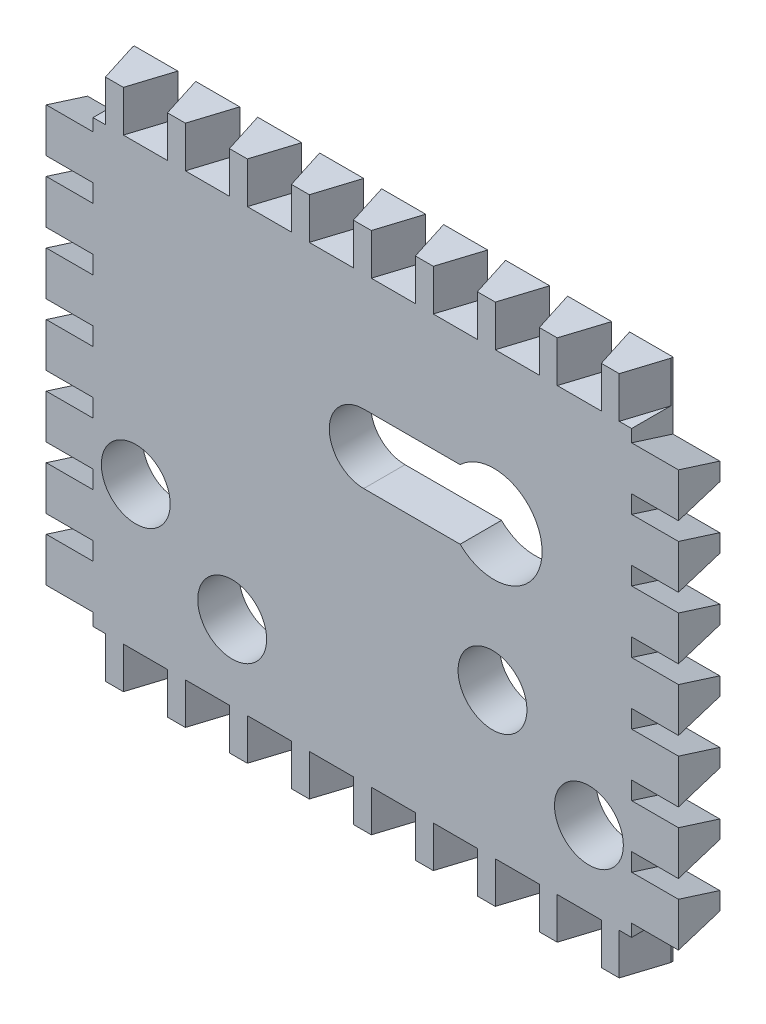
SolidWorks part; units mm, degrees
ref_plane "前视基准面" through (0, 0, 0) normal (0, 0, 1) x (1, 0, 0)
ref_plane "上视基准面" through (0, 0, 0) normal (0, 1, 0) x (1, 0, 0)
ref_plane "右视基准面" through (0, 0, 0) normal (1, 0, 0) x (0, 0, -1)
sketch "草图1" plane through (0, 0, 0) normal (0, 0, 1) x (1, 0, 0)
  line L1 (0, 0) -> (45.9, 0)
  line L2 (0, 0) -> (0, -38)
  line L3 (0, -38) -> (45.9, -38)
  line L4 (45.9, 0) -> (45.9, -38)
  dimension "D1" = 38
  dimension "D2" = 45.9
extrude "凸台-拉伸1" add sketch "草图1" along normal blind 3
sketch "草图2" plane through (0, 0, 3) normal (0, 0, 1) x (1, 0, 0)
  line L0 (22.95, 0) -> (22.95, -39.2263) construction
  line L1 (45.9, 0) -> (0, 0) construction
  line L2 (0, -19) -> (59.2839, -19) construction
  line L3 (0, 0) -> (0, -38) construction
sketch "草图3" plane through (0, 0, 0) normal (-1, 0, 0) x (0, 0, 1)
  line L2 (3, -7.1) -> (0, -6.15)
  line L7 (0, 0) -> (0, -38) construction
  line L8 (0, -4.85) -> (3, -3.9)
  line L9 (3, 0) -> (3, -39.2263) construction
  line L12 (0, -9.35) -> (3, -8.4)
  line L13 (0, -3.25) -> (4.2725, -3.25) construction
  line L15 (3, -11.6) -> (0, -10.65)
  line L16 (0, -10.65) -> (0, -13.85)
  line L17 (3, 0) -> (0, 0) construction
  line L18 (0, -13.85) -> (3, -12.9)
  line L19 (3, -12.9) -> (3, -11.6)
  line L20 (3, -16.1) -> (0, -15.15)
  line L21 (0, -15.15) -> (0, -18.35)
  line L22 (0, -18.35) -> (3, -17.4)
  line L23 (3, -17.4) -> (3, -16.1)
  line L24 (3, -20.6) -> (0, -19.65)
  line L25 (0, -19.65) -> (0, -22.85)
  line L26 (0, -22.85) -> (3, -21.9)
  line L27 (3, -21.9) -> (3, -20.6)
  line L28 (3, -25.1) -> (0, -24.15)
  line L29 (0, -24.15) -> (0, -27.35)
  line L30 (0, -27.35) -> (3, -26.4)
  line L31 (3, -26.4) -> (3, -25.1)
  line L32 (3, -29.6) -> (0, -28.65)
  line L33 (0, -28.65) -> (0, -31.85)
  line L34 (0, -31.85) -> (3, -30.9)
  line L35 (3, -30.9) -> (3, -29.6)
  line L36 (3, -34.1) -> (0, -33.15)
  line L40 (0, -6.15) -> (0, -9.35)
  line L45 (0, -10.65) -> (0, -33.15)
  line L49 (3, -8.4) -> (3, -7.1)
  line L52 (0, -4.85) -> (0, 0)
  line L53 (0, 0) -> (3, 0)
  line L54 (3, 0) -> (3, -3.9)
  line L55 (0, -33.15) -> (0, -38)
  line L56 (0, -38) -> (3, -38)
  line L57 (3, -38) -> (3, -34.1)
  line L58 (0, -36.35) -> (3, -35.4)
  line L59 (3, -34.1) -> (3, -11.6)
  line M1 (0, 0) -> (0, -38)
  line M2 (0, -38) -> (3, -38)
  line M3 (3, -38) -> (3, 0)
  line M4 (3, 0) -> (0, 0)
  dimension "D1" = 3.2
  dimension "D2" = 1.3
  dimension "D3" = 4.85
  dimension "D4" = 8
  dimension "D5" = 3.9
  dimension "D6" = 1.3
  dimension "D7" = 3.2
  dimension "D8" = 1.3
  dimension "D9" = 3.2
extrude "切除-拉伸3" cut sketch "草图3" against normal blind 3.4 contours L13 L54 M1 M4 | L13 L52 L8 M3 | L12 L2 M1 M3 | L18 L15 M1 M3 | L22 L20 M1 M3 | L26 L24 M1 M3 | L30 L28 M1 M3 | L34 L32 M1 M3 | L36 M3 M1 M2
sketch "草图5" plane through (45.9, 0, 0) normal (1, 0, 0) x (0, 0, -1)
  line L4 (-3.0028, 0) -> (-3.0028, -3.9)
  line L5 (0, 0) -> (0, -4.85)
  line L6 (0, -7.75) -> (-8.7917, -7.75) construction
  line L7 (-3, -7.1) -> (-3, -8.4)
  line L24 (-3, -34.1) -> (-3, -38)
  line L26 (0, -9.35) -> (0, -6.15)
  line L29 (-3.0028, 0) -> (0, 0)
  line L31 (0, -13.85) -> (0, -10.65)
  line L32 (-3, -11.6) -> (0, -10.65)
  line L33 (0, -33.15) -> (-3, -34.1)
  line L35 (-3, 0) -> (0, 0) construction
  line L36 (-1.5014, -4.375) -> (-1.5014, -9.405) construction
  line L67 (0, -9.35) -> (-3, -8.4)
  line L68 (0, -4.85) -> (-3.0028, -3.9)
  line L69 (-3, -7.1) -> (0, -6.15)
  line L73 (0, -33.15) -> (0, -38)
  line L74 (0, -38) -> (0, 0) construction
  line L75 (0, -38) -> (-3, -38)
  line L76 (-3, -11.6) -> (-3, -12.9)
  line L77 (0, -13.85) -> (-3, -12.9)
  line L78 (0, -18.35) -> (0, -15.15)
  line L79 (-3, -16.1) -> (0, -15.15)
  line L80 (-3, -16.1) -> (-3, -17.4)
  line L81 (0, -18.35) -> (-3, -17.4)
  line L82 (0, -22.85) -> (0, -19.65)
  line L83 (-3, -20.6) -> (0, -19.65)
  line L84 (-3, -20.6) -> (-3, -21.9)
  line L85 (0, -22.85) -> (-3, -21.9)
  line L86 (0, -27.35) -> (0, -24.15)
  line L87 (-3, -25.1) -> (0, -24.15)
  line L88 (-3, -25.1) -> (-3, -26.4)
  line L89 (0, -27.35) -> (-3, -26.4)
  line L90 (0, -31.85) -> (0, -28.65)
  line L91 (-3, -29.6) -> (0, -28.65)
  line L92 (-3, -29.6) -> (-3, -30.9)
  line L93 (0, -31.85) -> (-3, -30.9)
  dimension "D1" = 1.3
  dimension "D2" = 3.2
  dimension "D3" = 3
  dimension "D4" = 1.3
  dimension "D5" = 3.2
  dimension "D6" = 6
  dimension "D7" = 1.3
  dimension "D8" = 3.2
  dimension "D9" = 3.9
  dimension "D10" = 3.9
extrude "切除-拉伸4" cut sketch "草图5" against normal blind 3.4
sketch "草图7" plane through (0, -38, 0) normal (0, -1, 0) x (1, 0, 0)
  line L0 (5.6, 3) -> (8.8, 3)
  line L1 (0, 3) -> (59.2839, 3) construction
  line L2 (8.8, 3) -> (7.85, 0)
  line L3 (3.4, 0) -> (42.5, 0) construction
  line L4 (7.85, 0) -> (6.55, 0)
  line L5 (6.55, 0) -> (5.6, 3)
  line L6 (7.2, 3) -> (7.2, -0.6727) construction
  line L7 (0, 3) -> (0, 0) construction
  line L8 (4.3, 3) -> (3.35, 0)
  line L9 (3.35, 0) -> (0, 0)
  line L10 (0, 0) -> (0, 3)
  line L11 (0, 3) -> (4.3, 3)
  line L12 (11.05, 0) -> (10.1, 3)
  line L13 (10.1, 3) -> (13.3, 3)
  line L14 (13.3, 3) -> (12.35, 0)
  line L15 (12.35, 0) -> (11.05, 0)
  line L16 (15.55, 0) -> (14.6, 3)
  line L17 (14.6, 3) -> (17.8, 3)
  line L18 (17.8, 3) -> (16.85, 0)
  line L19 (16.85, 0) -> (15.55, 0)
  line L20 (20.05, 0) -> (19.1, 3)
  line L21 (19.1, 3) -> (22.3, 3)
  line L22 (22.3, 3) -> (21.35, 0)
  line L23 (21.35, 0) -> (20.05, 0)
  line L24 (24.55, 0) -> (23.6, 3)
  line L25 (23.6, 3) -> (26.8, 3)
  line L26 (26.8, 3) -> (25.85, 0)
  line L27 (25.85, 0) -> (24.55, 0)
  line L28 (29.05, 0) -> (28.1, 3)
  line L29 (28.1, 3) -> (31.3, 3)
  line L30 (31.3, 3) -> (30.35, 0)
  line L31 (30.35, 0) -> (29.05, 0)
  line L32 (33.55, 0) -> (32.6, 3)
  line L33 (32.6, 3) -> (35.8, 3)
  line L34 (35.8, 3) -> (34.85, 0)
  line L35 (34.85, 0) -> (33.55, 0)
  line L36 (38.05, 0) -> (37.1, 3)
  line L37 (37.1, 3) -> (40.3, 3)
  line L38 (40.3, 3) -> (39.35, 0)
  line L39 (39.35, 0) -> (38.05, 0)
  line L40 (22.95, 0) -> (22.95, 5.6535) construction
  line L41 (45.9, 0) -> (45.9, 3)
  line L42 (42.55, 0) -> (45.9, 0)
  line L43 (41.6, 3) -> (42.55, 0)
  line L44 (45.9, 3) -> (41.6, 3)
  dimension "D1" = 1.3
  dimension "D2" = 3.2
  dimension "D3" = 6.55
  dimension "D4" = 3.35
  dimension "D5" = 4.3
extrude "切除-拉伸5" cut sketch "草图7" against normal blind 3
sketch "草图8" plane through (0, 0, 0) normal (0, 1, 0) x (1, 0, 0)
  line L0 (6.55, 0) -> (5.6, -3)
  line L1 (42.5, 0) -> (3.4, 0) construction
  line L2 (0, -3) -> (59.2839, -3) construction
  line L3 (5.6, -3) -> (8.8, -3)
  line L4 (8.8, -3) -> (7.85, 0)
  line L5 (7.85, 0) -> (6.55, 0)
  line L6 (7.2, -3) -> (7.2, 2.5692) construction
  line L7 (3.35, 0) -> (4.3, -3)
  line L8 (4.3, -3) -> (0, -3)
  line L9 (0, -3) -> (0, 0)
  line L10 (0, 0) -> (3.35, 0)
  line L11 (12.35, 0) -> (11.05, 0)
  line L12 (11.05, 0) -> (10.1, -3)
  line L13 (10.1, -3) -> (13.3, -3)
  line L14 (13.3, -3) -> (12.35, 0)
  line L15 (16.85, 0) -> (15.55, 0)
  line L16 (15.55, 0) -> (14.6, -3)
  line L17 (14.6, -3) -> (17.8, -3)
  line L18 (17.8, -3) -> (16.85, 0)
  line L19 (21.35, 0) -> (20.05, 0)
  line L20 (20.05, 0) -> (19.1, -3)
  line L21 (19.1, -3) -> (22.3, -3)
  line L22 (22.3, -3) -> (21.35, 0)
  line L23 (25.85, 0) -> (24.55, 0)
  line L24 (24.55, 0) -> (23.6, -3)
  line L25 (23.6, -3) -> (26.8, -3)
  line L26 (26.8, -3) -> (25.85, 0)
  line L27 (30.35, 0) -> (29.05, 0)
  line L28 (29.05, 0) -> (28.1, -3)
  line L29 (28.1, -3) -> (31.3, -3)
  line L30 (31.3, -3) -> (30.35, 0)
  line L31 (34.85, 0) -> (33.55, 0)
  line L32 (33.55, 0) -> (32.6, -3)
  line L33 (32.6, -3) -> (35.8, -3)
  line L34 (35.8, -3) -> (34.85, 0)
  line L35 (39.35, 0) -> (38.05, 0)
  line L36 (38.05, 0) -> (37.1, -3)
  line L37 (37.1, -3) -> (40.3, -3)
  line L38 (40.3, -3) -> (39.35, 0)
  line L39 (22.95, 0) -> (22.95, -7.3642) construction
  line L40 (45.9, -3) -> (45.9, 0)
  line L41 (41.6, -3) -> (45.9, -3)
  line L42 (42.55, 0) -> (41.6, -3)
  line L43 (45.9, 0) -> (42.55, 0)
  dimension "D1" = 4.3
  dimension "D2" = 3.35
  dimension "D3" = 6.55
  dimension "D4" = 3.2
  dimension "D5" = 1.3
extrude "切除-拉伸6" cut sketch "草图8" against normal blind 3
sketch "草图9" plane through (0, 0, 3) normal (0, 0, 1) x (1, 0, 0)
  line L0 (45.9, -25.1) -> (45.9, -21.9) construction
  line L1 (35.8, -35) -> (32.6, -35) construction
  line L2 (45.9, -29.6) -> (45.9, -26.4) construction
  line L3 (40.3, -35) -> (37.1, -35) construction
  line L4 (22.95, 0) -> (22.95, -41.7829) construction
  line L5 (42.5, -11.6) -> (42.5, -12.9) construction
  line L6 (0, -19) -> (59.2839, -19) construction
  line L7 (30.0505, -14) -> (23.0505, -14) construction
  line L8 (30.0505, -16.5) -> (23.0505, -16.5)
  line L9 (30.0505, -11.5) -> (23.0505, -11.5)
  circle A0 centre (32.4, -24.5) radius 2.5
  circle A1 centre (39.4, -29.5) radius 2.5
  circle A3 centre (6.5, -24.5) radius 2.5
  circle A4 centre (13.5, -29.5) radius 2.5
  arc A5 (30.0505, -16.5) -> (30.0505, -11.5) centre (32.5, -14) ccw
  arc A7 (23.0505, -11.5) -> (23.0505, -16.5) centre (23.0505, -14) ccw
  point P27 (26.5505, -14)
  point P32 (0, 0)
  point P33 (0, 0)
  dimension "D1" = 5
  dimension "D2" = 5
  dimension "D3" = 13.5
  dimension "D4" = 10.5
  dimension "D5" = 6.5
  dimension "D6" = 5.5
  dimension "D7" = 2
  dimension "D8" = 7
  dimension "D9" = 10
  dimension "D10" = 5
  dimension "D11" = 7
  dimension "D12" = 5
extrude "切除-拉伸7" cut sketch "草图9" against normal through all
